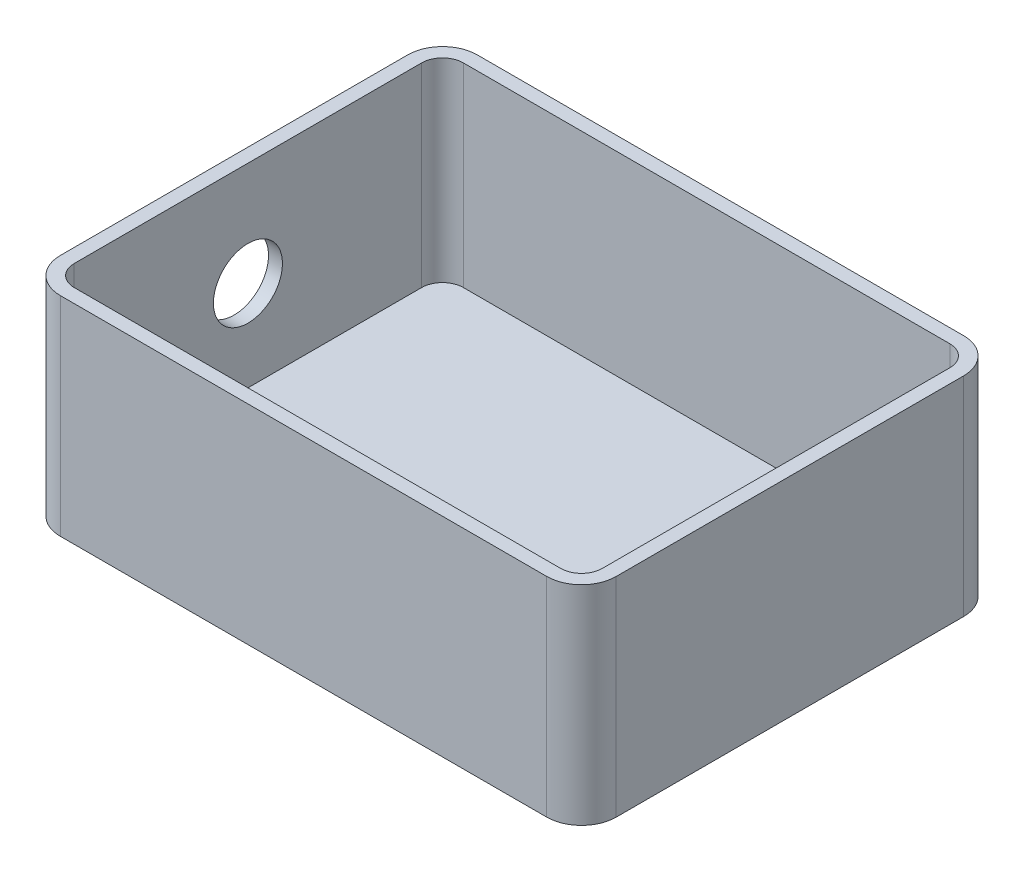
SolidWorks part; units mm, degrees
material "ABS"
ref_plane "Front Plane" through (0, 0, 0) normal (0, 0, 1) x (1, 0, 0)
ref_plane "Top Plane" through (0, 0, 0) normal (0, 1, 0) x (1, 0, 0)
ref_plane "Right Plane" through (0, 0, 0) normal (1, 0, 0) x (0, 0, -1)
sketch "Sketch1" plane through (0, 0, 0) normal (0, 1, 0) x (1, 0, 0)
  line L1 (-50.8, -38.1) -> (50.8, -38.1)
  line L2 (-50.8, -38.1) -> (-50.8, 38.1)
  line L3 (-50.8, 38.1) -> (50.8, 38.1)
  line L4 (50.8, -38.1) -> (50.8, 38.1)
  line L5 (-50.8, -38.1) -> (50.8, 38.1) construction
  line L6 (-50.8, 38.1) -> (50.8, -38.1) construction
  point P0 (0, 0)
  dimension "D1" = 101.6
  dimension "D2" = 76.2
extrude "Body" add sketch "Sketch1" along normal blind 38.1
fillet "Corner Fillets" radius 6.35 4 edges at (-50.8, 19.05, 38.1) (-50.8, 19.05, -38.1) (50.8, 19.05, -38.1) (50.8, 19.05, 38.1)
shell "Shell" thickness 2.54
sketch "Sketch2" plane through (-50.8, 0, 0) normal (-1, 0, 0) x (0, 0, 1)
  circle A0 centre (0, 19.0854) radius 6.3073
  point P2 (0, 0)
extrude "Cable Hole" cut sketch "Sketch2" against normal up to next
